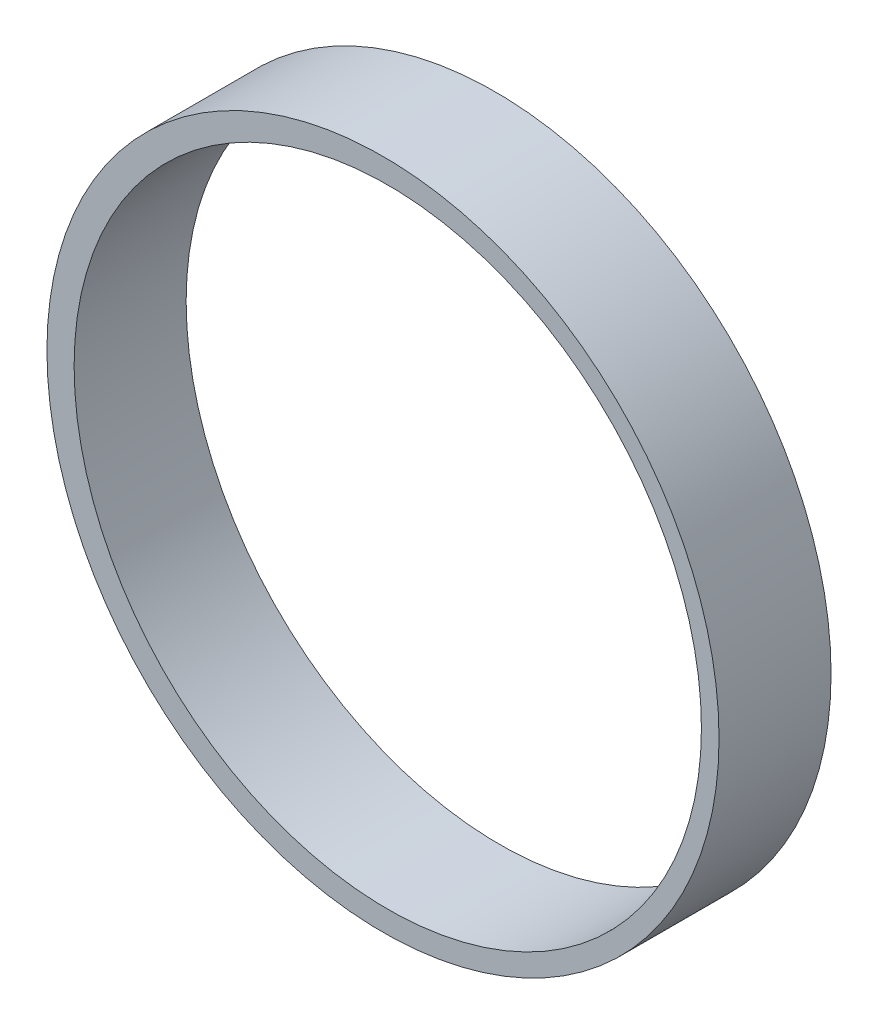
SolidWorks part; units mm, degrees
material "1060-H12"
ref_plane "Ebene vorne" through (0, 0, 0) normal (0, 0, 1) x (1, 0, 0)
ref_plane "Ebene oben" through (0, 0, 0) normal (0, 1, 0) x (1, 0, 0)
ref_plane "Ebene rechts" through (0, 0, 0) normal (1, 0, 0) x (0, 0, -1)
sketch "Skizze1" plane through (0, 0, 0) normal (0, 0, 1) x (1, 0, 0)
  circle A0 centre (0, 0) radius 15
  dimension "D1" = 30
extrude "Aufsatz-Linear austragen1" add sketch "Skizze1" along normal blind 5
sketch "Skizze2" plane through (0, 0, 5) normal (0, 0, 1) x (1, 0, 0)
  circle A0 centre (0.2133, 0) radius 14
  dimension "D1" = 28
extrude "Schnitt-Linear austragen1" cut sketch "Skizze2" against normal blind 5
